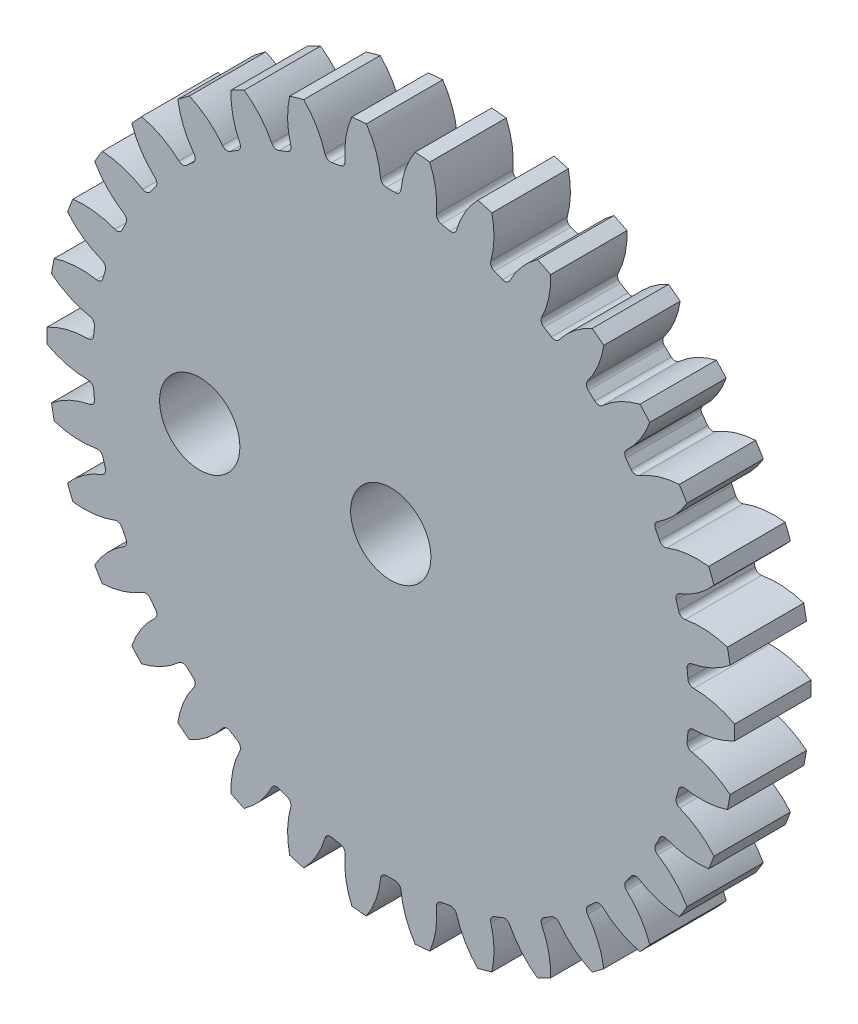
SolidWorks part; units mm, degrees
ref_plane "Front Plane" through (0, 0, 0) normal (0, 0, 1) x (1, 0, 0)
ref_plane "Top Plane" through (0, 0, 0) normal (0, 1, 0) x (1, 0, 0)
ref_plane "Right Plane" through (0, 0, 0) normal (1, 0, 0) x (0, 0, -1)
sketch "Sketch1" plane through (0, 0, 0) normal (0, 0, 1) x (1, 0, 0)
  circle A0 centre (0, 0) radius 8.5 construction
  circle A1 centre (0, 0) radius 9
  dimension "D1" = 17
  dimension "D2" = 18
extrude "Boss-Extrude1" add sketch "Sketch1" along normal mid plane 2
sketch "Sketch3" plane through (0, 0, 0) normal (0, 0, 1) x (1, 0, 0)
  line L0 (0, 9) -> (0, 0) construction
  line L1 (0, 0) -> (1.6537, 8.8468) construction
  line L2 (0, 0) -> (0.8304, 8.9616) construction
  line L3 (-0.2581, 7.7957) -> (0, 0) construction
  line L4 (-0.3926, 8.4909) -> (0.3926, 8.4909) construction
  line L5 (0.3926, 8.4909) -> (1.1743, 8.4185) construction
  line L6 (-0.5712, 8.9819) -> (0, 7.4124) construction
  circle A0 centre (0, 0) radius 8 construction
  arc A1 (0.2581, 7.7957) -> (-0.2581, 7.7957) centre (0, 0) ccw
  circle A2 centre (0, 0) radius 9 construction
  arc A3 (-0.6399, 8.9772) -> (-0.2581, 7.7957) centre (-2.5072, 7.7213) cw
  circle A5 centre (0, 0) radius 9 construction
  arc A6 (0.6399, 8.9772) -> (0.2581, 7.7957) centre (2.5072, 7.7213) ccw
  circle A7 centre (0, 0) radius 8.5 construction
  arc A9 (0.6399, 8.9772) -> (-0.6399, 8.9772) centre (0, 0) ccw
  dimension "D1" = 10.588
  dimension "D2" = 1
  dimension "D3" = 1.2
  dimension "D4" = 0.2
  dimension "D5" = 20
extrude "Cut-Extrude1" cut sketch "Sketch3" against normal through all both and the other way through all
fillet "Fillet1" radius 0.15 2 edges at (-0.2581, 7.7957, 0) (0.2581, 7.7957, 0)
pattern_circular "CirPattern1" count 34 over 360 about axis through (0, 0, 0) along (0, 0, 1) of "Fillet1", "Cut-Extrude1"
sketch "Sketch4" plane through (0, 0, 1) normal (0, 0, 1) x (1, 0, 0)
  circle A0 centre (0, 0) radius 1.05
  dimension "D1" = 2.1
extrude "Cut-Extrude2" cut sketch "Sketch4" against normal through all both
sketch "Sketch5" plane through (0, 0, 1) normal (0, 0, 1) x (1, 0, 0)
  line L0 (-5, 0) -> (0, 0) construction
  circle A0 centre (-5, 0) radius 1.05
  dimension "D1" = 2.1
  dimension "D2" = 5
extrude "Cut-Extrude3" cut sketch "Sketch5" against normal blind 10
equation "\"module\"= 0.5mm"
equation "\"number of teeth\"= 34"
equation "\"pressure angle\"= 20"
equation "\"D1@Sketch1\"= \"module\" * \"number of teeth\""
equation "\"D2@Sketch1\"=(\"number of teeth\" + 2) * \"module\" "
equation "\"D1@Sketch3\"=360 / \"number of teeth\""
equation "\"D3@Sketch3\"= \"module\"  * if( \"module\" => 1.25,2.25,2.4)"
equation "\"D5@Sketch3\"=\"pressure angle\""
equation "\"D1@Fillet1\"=0.3 * \"module\""
equation "\"D1@CirPattern1\"=\"number of teeth\""
equation "\"D1@Chamfer1\"=\"module\""
